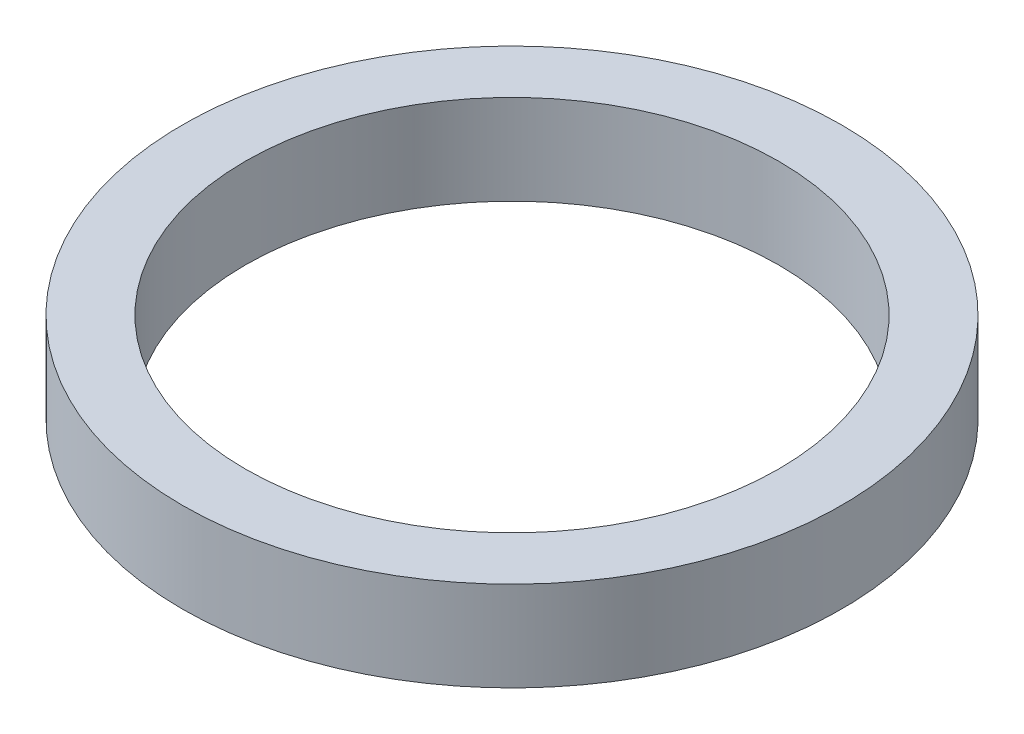
SolidWorks part; units mm, degrees
material "1023 Carbon Steel Sheet (SS)"
ref_plane "Front Plane" through (0, 0, 0) normal (0, 0, 1) x (1, 0, 0)
ref_plane "Top Plane" through (0, 0, 0) normal (0, 1, 0) x (1, 0, 0)
ref_plane "Right Plane" through (0, 0, 0) normal (1, 0, 0) x (0, 0, -1)
sketch "Sketch1" plane through (0, 0, 0) normal (0, 1, 0) x (1, 0, 0)
  circle A0 centre (0, 0) radius 8.9
  circle A1 centre (0, 0) radius 11
  dimension "D1" = 22
  dimension "D2" = 17.8
extrude "Boss-Extrude1" add sketch "Sketch1" along normal blind 3
